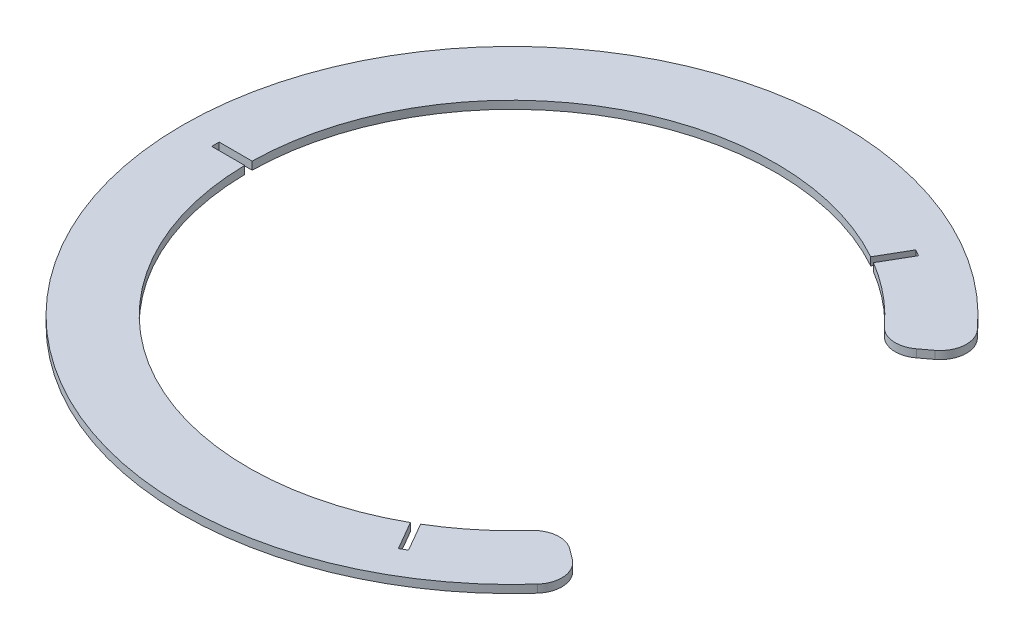
SolidWorks part; units mm, degrees
ref_plane "Front Plane" through (0, 0, 0) normal (0, 0, 1) x (1, 0, 0)
ref_plane "Top Plane" through (0, 0, 0) normal (0, 1, 0) x (1, 0, 0)
ref_plane "Right Plane" through (0, 0, 0) normal (1, 0, 0) x (0, 0, -1)
sketch "Sketch1" plane through (0, 0, 0) normal (0, 1, 0) x (1, 0, 0)
  circle A0 centre (0, 0) radius 125
  dimension "D1" = 250
extrude "Boss-Extrude1" add sketch "Sketch1" along normal blind 3
sketch "Sketch2" plane through (0, 3, 0) normal (0, 1, 0) x (1, 0, 0)
  circle A0 centre (0, 0) radius 100
  dimension "D1" = 200
extrude "Cut-Extrude1" cut sketch "Sketch2" against normal blind 3
sketch "Sketch3" plane through (0, 3, 0) normal (0, 1, 0) x (1, 0, 0)
  line L0 (182.6141, 0) -> (-182.6141, 0) construction
  line L2 (0, -164.1797) -> (0, 164.1797) construction
  line L3 (-87.5, -1.415) -> (-112.5, -1.415)
  line L4 (-87.5, -1.415) -> (-87.5, 1.415)
  line L5 (-87.5, 1.415) -> (-112.5, 1.415)
  line L6 (-112.5, -1.415) -> (-112.5, 1.415)
  line L7 (-87.5, -1.415) -> (-112.5, 1.415) construction
  line L8 (-87.5, 1.415) -> (-112.5, -1.415) construction
  circle A0 centre (0, 0) radius 100 construction
  point P0 (-100, 0)
  point P4 (0, 0)
  point P7 (0, 0)
  dimension "D1" = 25
  dimension "D2" = 2.83
extrude "Cut-Extrude2" cut sketch "Sketch3" against normal blind 3
pattern_circular "CirPattern1" count 3 over 360 about axis through (0, 0, 0) along (0, 1, 0) of "Cut-Extrude2"
sketch "Sketch4" plane through (0, 3, 0) normal (0, 1, 0) x (1, 0, 0)
  line L0 (80, 60) -> (80, -60) construction
  line L1 (80, -60) -> (99.9826, -75.0233)
  line L2 (80, 60) -> (100, 75)
  arc A0 (80, 60) -> (80, -60) centre (0, 0) cw
  arc A1 (51.2204, -85.8864) -> (51.2204, 85.8864) centre (0, 0) ccw construction
  circle A2 centre (0, 0) radius 125 construction
  arc A3 (100, 75) -> (99.9826, -75.0233) centre (0, 0) cw
  dimension "D1" = 120
extrude "Cut-Extrude3" cut sketch "Sketch4" against normal blind 3
fillet "Fillet1" radius 10 4 edges at (80, 1.5, 60) (99.9826, 1.5, 75.0233) (100, 1.5, -75) (80, 1.5, -60)
equation "\"D2@Sketch3\"=3-0.17"
